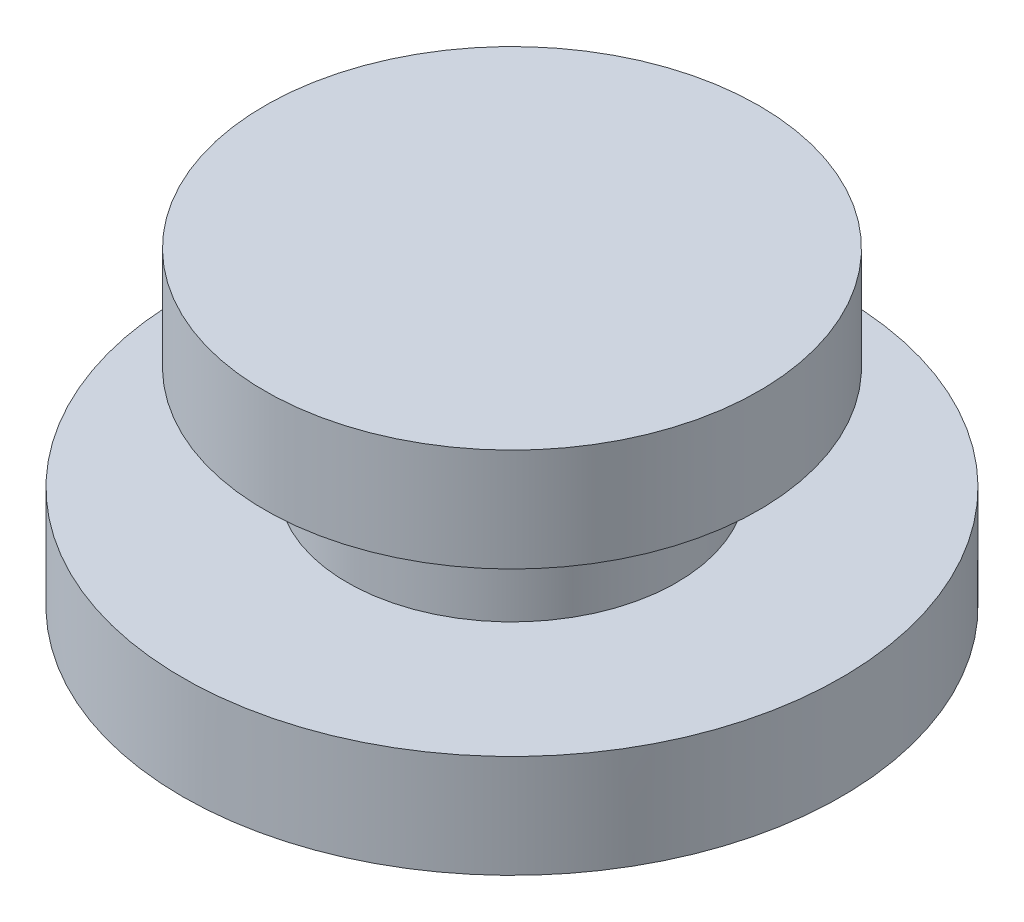
SolidWorks part; units mm, degrees
material "Cast Alloy Steel"
ref_plane "Front Plane" through (0, 0, 0) normal (0, 0, 1) x (1, 0, 0)
ref_plane "Top Plane" through (0, 0, 0) normal (0, 1, 0) x (1, 0, 0)
ref_plane "Right Plane" through (0, 0, 0) normal (1, 0, 0) x (0, 0, -1)
sketch "Sketch2" plane through (0, 0, 0) normal (1, 0, 0) x (0, 0, -1)
  line L0 (0, 110) -> (120, 110)
  line L1 (120, 110) -> (120, 60)
  line L2 (120, 60) -> (80, 60)
  line L3 (80, 60) -> (80, 9.4744)
  line L4 (80, 9.4744) -> (160, 9.4744)
  line L5 (160, 9.4744) -> (160, -40.5256)
  line L6 (160, -40.5256) -> (50, -70)
  line L7 (50, -70) -> (50, -110)
  line L8 (50, -110) -> (0, -110)
  line L9 (0, -110) -> (0, 110)
  point P2 (80, 34.7372)
  dimension "D1" = 50
  dimension "D2" = 160
  dimension "D3" = 120
  dimension "D4" = 50
  dimension "D5" = 50
  dimension "D6" = 220
  dimension "D7" = 40
  dimension "D8" = 105
  dimension "D9" = 80
  dimension "D10" = 110
  dimension "D11" = 0
revolve "Revolve1" add sketch "Sketch2" angle 360 about L9
